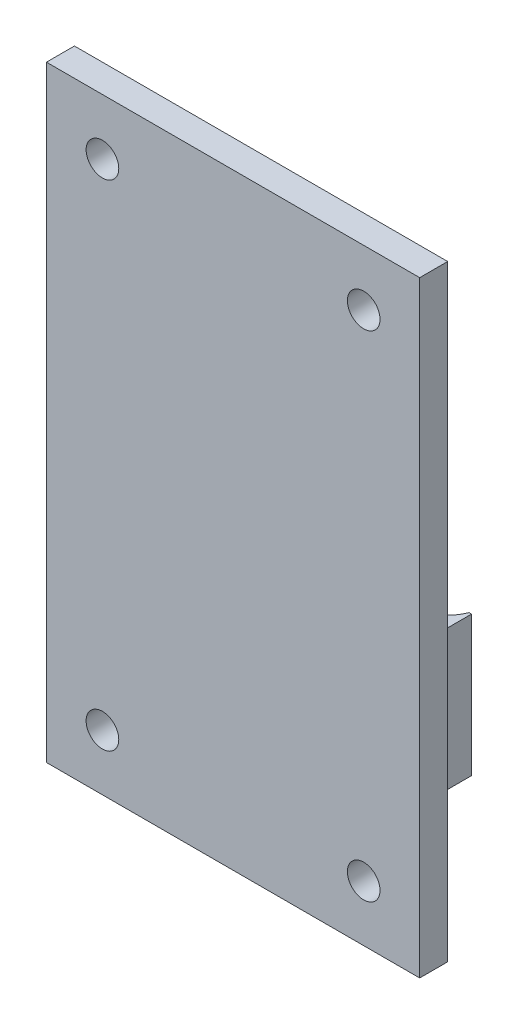
SolidWorks part; units mm, degrees
ref_plane "Front Plane" through (0, 0, 0) normal (0, 0, 1) x (1, 0, 0)
ref_plane "Top Plane" through (0, 0, 0) normal (0, 1, 0) x (1, 0, 0)
ref_plane "Right Plane" through (0, 0, 0) normal (1, 0, 0) x (0, 0, -1)
sketch "Sketch1" plane through (0, 0, 0) normal (0, 0, 1) x (1, 0, 0)
  line L0 (6, 59) -> (6, 6) construction
  line L1 (0, 0) -> (40, 0)
  line L2 (0, 0) -> (0, 65)
  line L3 (0, 65) -> (40, 65)
  line L4 (40, 0) -> (40, 65)
  line L5 (6, 6) -> (34, 6) construction
  line L6 (34, 6) -> (34, 59) construction
  line L7 (34, 59) -> (6, 59) construction
  circle A0 centre (6, 59) radius 1.75
  circle A1 centre (34, 59) radius 1.75
  circle A2 centre (6, 6) radius 1.75
  circle A3 centre (34, 6) radius 1.75
  dimension "D3" = 3.5
  dimension "D1" = 40
  dimension "D2" = 65
  dimension "D4" = 6
  dimension "D5" = 6
  dimension "D6" = 6
  dimension "D7" = 6
extrude "Boss-Extrude1" add sketch "Sketch1" along normal blind 3
sketch "Sketch2" plane through (0, 0, 0) normal (0, -1, 0) x (-1, 0, 0)
  line L0 (0, 0) -> (-40, 0) construction
  line L1 (-24, 0) -> (-16, 0)
  line L2 (-24, 0) -> (-24, 18.5582)
  line L3 (-24, 20) -> (-16, 20) construction
  line L4 (-16, 0) -> (-16, 18.5582)
  line L5 (0, -3) -> (-40, -3) construction
  line L6 (-16.2689, 18.5582) -> (-16, 18.5582)
  line L7 (-23.7311, 18.5582) -> (-24, 18.5582)
  arc A0 (-23.7311, 18.5582) -> (-16.2689, 18.5582) centre (-20, 20) ccw
  point P8 (-20, -3)
  dimension "D1" = 20
  dimension "D2" = 4
  dimension "D3" = 8
extrude "Boss-Extrude2" add sketch "Sketch2" against normal blind 15
